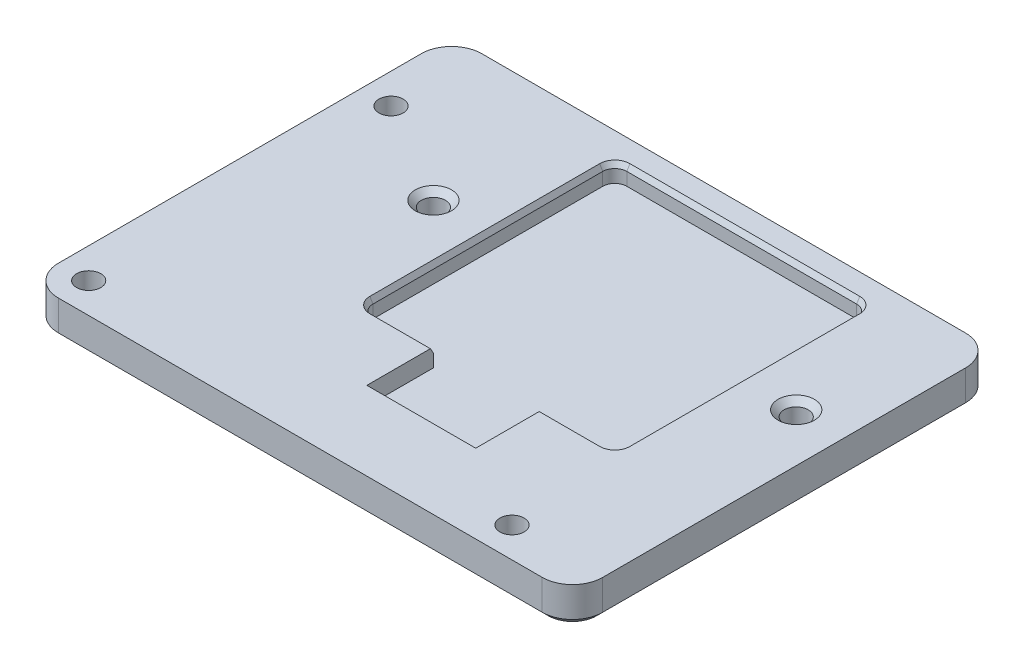
SolidWorks part; units mm, degrees
ref_plane "Спереди" through (0, 0, 0) normal (0, 0, 1) x (1, 0, 0)
ref_plane "Сверху" through (0, 0, 0) normal (0, 1, 0) x (1, 0, 0)
ref_plane "Справа" through (0, 0, 0) normal (1, 0, 0) x (0, 0, -1)
sketch "Эскиз1" plane through (0, 0, 0) normal (0, 1, 0) x (1, 0, 0)
  line L1 (-40, -30) -> (50, -30)
  line L2 (-40, -30) -> (-40, 40)
  line L3 (-40, 40) -> (50, 40)
  line L4 (50, -30) -> (50, 40)
  line L7 (-35, -25) -> (35, -25) construction
  line L8 (-35, -25) -> (-35, 25) construction
  line L9 (-35, 25) -> (35, 25) construction
  line L10 (35, -25) -> (35, 25) construction
  circle A0 centre (-35, 25) radius 2
  circle A1 centre (35, 25) radius 2
  circle A2 centre (-35, -25) radius 2
  circle A3 centre (35, -25) radius 2
  point P0 (0, 0)
  point P6 (0, 0)
  point P12 (0, 0)
  point P15 (0.1928, -0.186)
  dimension "D3" = 4
  dimension "D4" = 70
  dimension "D1" = 90
  dimension "D2" = 70
  dimension "D5" = 50
  dimension "D6" = 50
  dimension "D7" = 30
extrude "Бобышка-Вытянуть1" add sketch "Эскиз1" along normal blind 6 contours L1 L4 L3 L2 A3 A2 A1 A0 | A1
fillet "Скругление1" radius 5 4 edges at (-40, 3, -40) (50, 3, -40) (50, 3, 30) (-40, 3, 30)
sketch "Эскиз2" plane through (0, 6, 0) normal (0, 1, 0) x (1, 0, 0)
  line L1 (-9, -6) -> (33, -6)
  line L2 (-9, -6) -> (-9, 36)
  line L3 (-9, 36) -> (33, 36)
  line L4 (33, -6) -> (33, 36)
  line L5 (12, 36) -> (12, -6) construction
  line L6 (-9, 15) -> (33, 15) construction
  circle A0 centre (35, -25) radius 2 construction
  circle A1 centre (-35, -25) radius 2 construction
  point P0 (12, 15)
  point P8 (0, 0)
  point P9 (0, 0)
  dimension "D3" = 23
  dimension "D5" = 47
  dimension "D6" = 40
  dimension "D1" = 42
  dimension "D2" = 42
  dimension "D4" = 40
extrude "Вырез-Вытянуть1" cut sketch "Эскиз2" against normal blind 3
sketch "Эскиз3" plane through (0, 6, 0) normal (0, 1, 0) x (1, 0, 0)
  line L0 (12, 36) -> (12, -32.6922) construction
  line L1 (33, 36) -> (-9, 36) construction
  line L2 (-9, -6) -> (33, -6) construction
  line L3 (3, -15) -> (21, -15)
  line L4 (3, -15) -> (3, 3)
  line L5 (3, 3) -> (21, 3)
  line L6 (21, -15) -> (21, 3)
  line L7 (12, 3) -> (12, -15) construction
  line L8 (3, -6) -> (21, -6) construction
  point P4 (12, -6)
  dimension "D1" = 18
  dimension "D2" = 18
extrude "Вырез-Вытянуть2" cut sketch "Эскиз3" against normal blind 3
fillet "Скругление2" radius 2 4 edges at (33, 4.5, 6) (-9, 4.5, 6) (-9, 4.5, -36) (33, 4.5, -36)
chamfer "Фаска1" distance 2 angle 45 1 edges at (12, 6, 15)
sketch "Эскиз4" plane through (0, 6, 0) normal (0, 1, 0) x (1, 0, 0)
  line L0 (12, 36) -> (-9, 15) construction
  line L1 (31, 36) -> (-7, 36) construction
  line L2 (-9, 34) -> (-9, -4) construction
  line L3 (-9, 15) -> (44.3239, 15) construction
  line L4 (44.3239, 15) -> (-42.5122, 15) construction
  line L5 (12, -17) -> (12, 32.404) construction
  line L6 (21, -17) -> (3, -17) construction
  circle A0 centre (-18, 15) radius 2
  circle A1 centre (42, 15) radius 2
  dimension "D1" = 30
  dimension "D2" = 4
extrude "Вырез-Вытянуть3" cut sketch "Эскиз4" against normal blind 5
chamfer "Фаска2" distance 1 angle 45 2 edges at (42, 6, -17) (-18, 6, -13)
chamfer "Фаска3" distance 1 angle 45 11 edges at (-38.5355, 0, 28.5355) (5, 0, 30) (48.5355, 0, 28.5355) (50, 0, -5) (48.5355, 0, -38.5355) (5, 0, -40) (-38.5355, 0, -38.5355) (-40, 0, -5) (-35, 0, -23) (-35, 0, 27) (35, 0, 27)
sketch "Эскиз5" plane through (0, 3, 0) normal (0, 1, 0) x (1, 0, 0)
  line L0 (12, 36) -> (12, 4.7203) construction
  line L1 (31, 36) -> (-7, 36) construction
  line L2 (12, 4.7203) -> (33, 15) construction
  line L3 (33, -4) -> (33, 34) construction
  line L4 (33, 15) -> (-10.4557, 15) construction
  circle A0 centre (12, 15) radius 5
  point P2 (0, 0)
extrude "Бобышка-Вытянуть2" [suppressed] add sketch "Эскиз5" along normal blind 100
chamfer "Фаска4" distance 0.5 angle 60 9 edges at (26, 6, 6) (32.4142, 6, 5.4142) (33, 6, -15) (32.4142, 6, -35.4142) (12, 6, -36) (-2, 6, 6) (-8.4142, 6, -35.4142) (-8.4142, 6, 5.4142) (-9, 6, -15)
